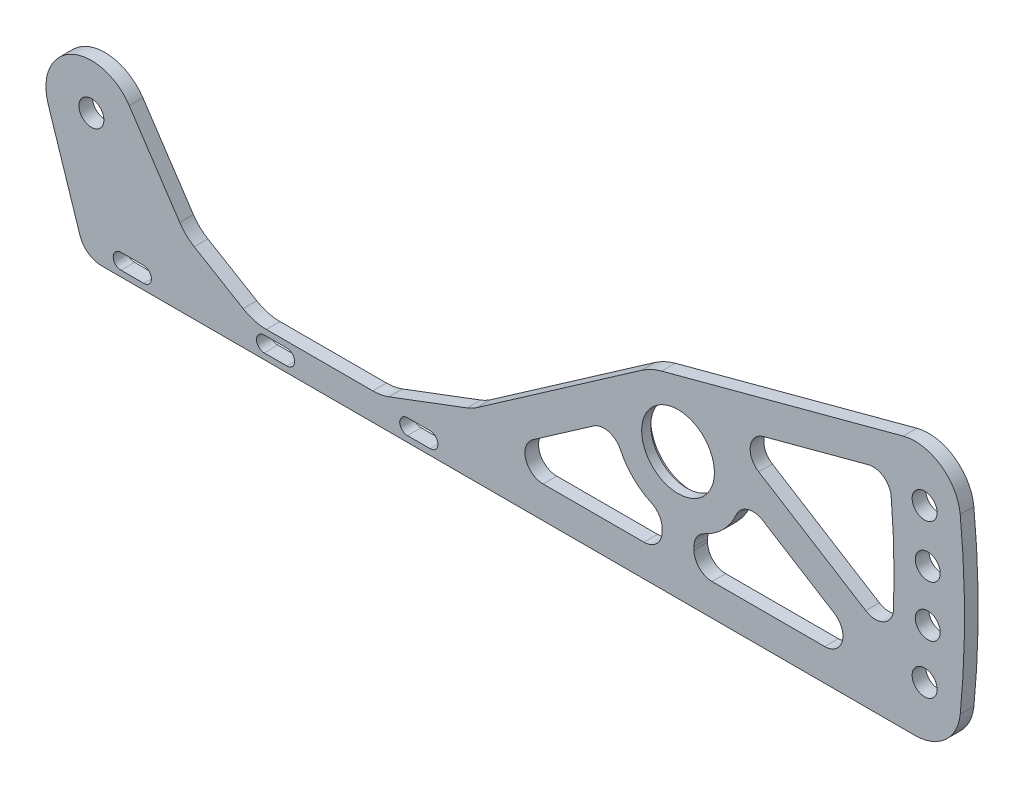
SolidWorks part; units mm, degrees
ref_plane "Спереди" through (0, 0, 0) normal (0, 0, 1) x (1, 0, 0)
ref_plane "Сверху" through (0, 0, 0) normal (0, 1, 0) x (1, 0, 0)
ref_plane "Справа" through (0, 0, 0) normal (1, 0, 0) x (0, 0, -1)
sketch "Эскиз1" plane through (0, 0, 0) normal (0, 0, 1) x (1, 0, 0)
  line L0 (-31.9542, -25) -> (253.1565, -25) construction
  line L1 (9, 35.6094) -> (9, -47.5785) construction
  line L2 (-39.2405, -28) -> (262.4545, -28) construction
  line L3 (-31.9542, -22) -> (262.4545, -22) construction
  line L4 (-9.5085, -3.0964) -> (-1.3987, -28)
  line L5 (8.3266, 5.5379) -> (20.6752, -13.0291)
  line L6 (-26.4187, 0) -> (187.6558, 0) construction
  line L7 (121.0002, 11.4893) -> (83.7656, -14.4365)
  line L8 (63.7181, -22) -> (35.7314, -22)
  line L9 (0, 0) -> (183.9142, 5.6191) construction
  line L10 (0, 0) -> (183.9142, -5.6191) construction
  line L11 (0, 0) -> (183.2281, -16.8363) construction
  line L12 (0, 0) -> (183.2281, 16.8363) construction
  line L13 (125.388, 13.526) -> (189.5368, 30.6561)
  line L14 (-1.3987, -28) -> (189.9474, -28)
  line L15 (40.5, -17.0585) -> (40.5, -35.954) construction
  line L16 (72, -17.0585) -> (72, -35.954) construction
  line L17 (20.6752, -13.0291) -> (35.7314, -22)
  line L18 (83.7656, -14.4365) -> (63.7181, -22)
  arc A0 (8.3266, 5.5379) -> (-9.5085, -3.0964) centre (0, 0) ccw
  circle A1 centre (129, 0) radius 8
  arc A2 (125.388, 13.526) -> (121.0002, 11.4893) centre (129, 0) ccw
  circle A3 centre (0, 0) radius 184 construction
  arc A4 (189.9474, -28) -> (189.5368, 30.6561) centre (0, 0) ccw
  dimension "D1" = 20
  dimension "D2" = 25
  dimension "D3" = 9
  dimension "D6" = 16
  dimension "D8" = 28
  dimension "D9" = 368
  dimension "D10" = 31.5
  dimension "D16" = 192
  dimension "D4" = 6
  dimension "D5" = 3
  dimension "D7" = 129
  dimension "D11" = 3.5
  dimension "D12" = 3.5
  dimension "D13" = 3.5
  dimension "D14" = 1.75
  dimension "D15" = 31.5
extrude "Бобышка-Вытянуть1" add sketch "Эскиз1" along normal blind 3
hole_wizard "Отверстие с зазором M31" positions "Эскиз3" profile "Эскиз2" hole size "M3" standard "Ansi Metric" end condition through all
sketch "Эскиз3" plane through (0, 0, 3) normal (0, 0, 1) x (1, 0, 0)
  line L0 (-31.9542, -25) -> (253.1565, -25) construction
  line L1 (9, 35.6094) -> (9, -47.5785) construction
  line L2 (40.5, -17.0585) -> (40.5, -35.954) construction
  line L3 (72, -17.0585) -> (72, -35.954) construction
  point P0 (9, -25)
  point P6 (40.5, -25)
  point P10 (72, -25)
sketch "Эскиз2" plane through (9, -25, 3) normal (1, 0, 0) x (0, -1, 0)
  line L0 (0, 0) -> (0, 3)
  line L1 (0, 3) -> (1.7, 3)
  line L2 (1.7, 3) -> (1.7, 0)
  line L5 (1.7, 0) -> (0, 0)
  line L11 (0, -6.35) -> (0, 107.95) construction
  dimension "Диаметр сквозного отверстия" = 3.4
  dimension "Глубина сквозного отверстия" = 3
hole_wizard "Отверстие с зазором M51" positions "Эскиз5" profile "Эскиз4" hole size "M5" standard "Ansi Metric" end condition through all
sketch "Эскиз5" plane through (0, 0, 3) normal (0, 0, 1) x (1, 0, 0)
  point P2 (0, 0)
sketch "Эскиз4" plane through (0, 0, 3) normal (1, 0, 0) x (0, -1, 0)
  line L0 (0, 0) -> (0, 3)
  line L1 (0, 3) -> (2.75, 3)
  line L2 (2.75, 3) -> (2.75, 0)
  line L5 (2.75, 0) -> (0, 0)
  line L11 (0, -6.35) -> (0, 107.95) construction
  dimension "Диаметр сквозного отверстия" = 5.5
  dimension "Глубина сквозного отверстия" = 3
hole_wizard "Отверстие с зазором M52" positions "Эскиз7" profile "Эскиз6" hole size "M5" standard "Ansi Metric" end condition through all
sketch "Эскиз7" plane through (0, 0, 3) normal (0, 0, 1) x (1, 0, 0)
  point P0 (183.2281, 16.8363)
  point P3 (183.9142, 5.6191)
  point P6 (183.9142, -5.6191)
  point P9 (183.2281, -16.8363)
sketch "Эскиз6" plane through (183.2281, 16.8363, 3) normal (1, 0, 0) x (0, -1, 0)
  line L0 (0, 0) -> (0, 3)
  line L1 (0, 3) -> (2.75, 3)
  line L2 (2.75, 3) -> (2.75, 0)
  line L5 (2.75, 0) -> (0, 0)
  line L11 (0, -6.35) -> (0, 107.95) construction
  dimension "Диаметр сквозного отверстия" = 5.5
  dimension "Глубина сквозного отверстия" = 3
fillet "Скругление1" radius 10 6 edges at (35.7314, -22, 1.5) (20.6752, -13.0291, 1.5) (63.7181, -22, 1.5) (83.7656, -14.4365, 1.5) (189.9474, -28, 1.5) (189.5368, 30.6561, 1.5)
fillet "Скругление2" radius 5 1 edges at (-1.3987, -28, 1.5)
sketch "Эскиз8" plane through (0, 0, 3) normal (0, 0, 1) x (1, 0, 0)
  line L0 (138.9079, 9.8911) -> (175.4042, 19.6369)
  line L1 (178.5224, 27.7149) -> (125.388, 13.526) construction
  line L2 (142.9717, -0.889) -> (175.2463, -21)
  line L3 (175.2463, -21) -> (132.5, -21)
  line L4 (2.2315, -28) -> (181.1077, -28) construction
  line L5 (115.0501, -1.1834) -> (86.5894, -21)
  line L6 (121.0002, 11.4893) -> (84.7863, -13.7258) construction
  line L8 (125.5, -13.5554) -> (125.5, -21)
  line L9 (132.5, -13.5554) -> (132.5, -21)
  line L10 (138.9079, 9.8911) -> (176.0039, -13.2243)
  line L11 (125.5, -21) -> (86.5894, -21)
  arc A0 (115.0501, -1.1834) -> (125.5, -13.5554) centre (129, 0) ccw
  arc A1 (125.388, 13.526) -> (121.0002, 11.4893) centre (129, 0) ccw construction
  arc A2 (176.0039, -13.2243) -> (175.4042, 19.6369) centre (0, 0) ccw
  arc A3 (132.5, -13.5554) -> (142.9717, -0.889) centre (129, 0) ccw
  dimension "D2" = 353
  dimension "D1" = 7
  dimension "D3" = 7
  dimension "D4" = 7
  dimension "D5" = 7
  dimension "D6" = 3.5
  dimension "D7" = 7
extrude "Вырез-Вытянуть1" cut sketch "Эскиз8" against normal through all
fillet "Скругление3" radius 4 11 edges at (86.5894, -21, 1.5) (125.5, -21, 1.5) (115.0501, -1.1834, 1.5) (125.5, -13.5554, 1.5) (132.5, -21, 1.5) (132.5, -13.5554, 1.5) (142.9717, -0.889, 1.5) (175.2463, -21, 1.5) (176.0039, -13.2243, 1.5) (175.4042, 19.6369, 1.5) (138.9079, 9.8911, 1.5)
sketch "Эскиз9" plane through (0, 0, 0) normal (0, 0, -1) x (-1, 0, 0)
  circle A0 centre (-129, 0) radius 9
  dimension "D1" = 18
extrude "Вырез-Вытянуть2" cut sketch "Эскиз9" against normal blind 1
sketch "Эскиз10" plane through (0, 0, 3) normal (0, 0, 1) x (1, 0, 0)
  line L0 (6.5, -25) -> (11.5, -25) construction
  line L1 (6.5, -23.3) -> (11.5, -23.3)
  line L2 (6.5, -26.7) -> (11.5, -26.7)
  line L3 (38, -25) -> (43, -25) construction
  line L4 (38, -23.3) -> (43, -23.3)
  line L5 (38, -26.7) -> (43, -26.7)
  line L6 (69.5, -25) -> (74.5, -25) construction
  line L7 (69.5, -23.3) -> (74.5, -23.3)
  line L8 (69.5, -26.7) -> (74.5, -26.7)
  arc A0 (6.5, -23.3) -> (6.5, -26.7) centre (6.5, -25) ccw
  arc A1 (11.5, -26.7) -> (11.5, -23.3) centre (11.5, -25) ccw
  circle A2 centre (9, -25) radius 1.7 construction
  arc A3 (38, -23.3) -> (38, -26.7) centre (38, -25) ccw
  arc A4 (43, -26.7) -> (43, -23.3) centre (43, -25) ccw
  circle A5 centre (40.5, -25) radius 1.7 construction
  arc A6 (69.5, -23.3) -> (69.5, -26.7) centre (69.5, -25) ccw
  arc A7 (74.5, -26.7) -> (74.5, -23.3) centre (74.5, -25) ccw
  circle A8 centre (72, -25) radius 1.7 construction
  point P2 (9, -25)
  point P12 (40.5, -25)
  point P22 (72, -25)
  dimension "D1" = 5
  dimension "D2" = 5
  dimension "D3" = 5
extrude "Вырез-Вытянуть3" cut sketch "Эскиз10" against normal through all
equation "\"D12@Эскиз1\"=\"D11@Эскиз1\""
equation "\"D13@Эскиз1\"=\"D11@Эскиз1\""
equation "\"D14@Эскиз1\"=\"D11@Эскиз1\"/2"
